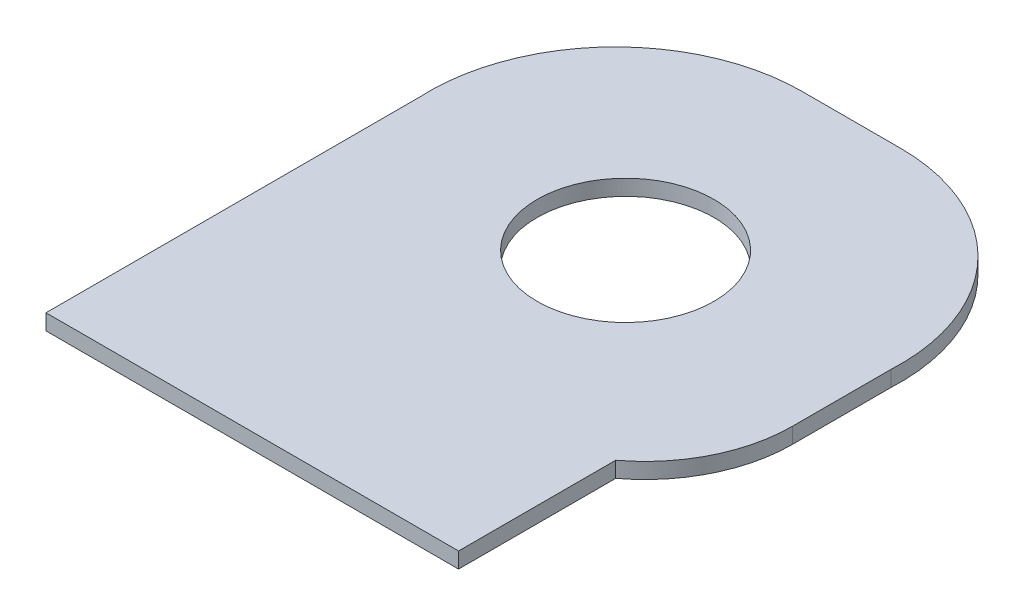
SolidWorks part; units mm, degrees
ref_plane "Plan de face" through (0, 0, 0) normal (0, 0, 1) x (1, 0, 0)
ref_plane "Plan de dessus" through (0, 0, 0) normal (0, 1, 0) x (1, 0, 0)
ref_plane "Plan de droite" through (0, 0, 0) normal (1, 0, 0) x (0, 0, -1)
sketch "Esquisse1" plane through (0, 0, 0) normal (0, 1, 0) x (1, 0, 0)
  line L0 (-24, 9) -> (-24, -29)
  line L1 (-24, -29) -> (18, -29)
  line L2 (18, -29) -> (18, -13)
  line L3 (24, -1) -> (24, 9)
  line L4 (-5, 29) -> (5, 29)
  line L5 (0, 29) -> (0, -29) construction
  line L6 (24, 0) -> (-24, 0) construction
  arc A0 (-5, 29) -> (-24, 9) centre (-5, 9.975) ccw
  arc A1 (5, 29) -> (24, 9) centre (5, 9.975) cw
  arc A2 (24, -1) -> (18, -13) centre (9, -1) cw
  circle A3 centre (0, 6) radius 9
  point P14 (0, 0)
  dimension "D1" = 42
  dimension "D2" = 38
  dimension "D8" = 18
  dimension "D3" = 16
  dimension "D4" = 10
  dimension "D5" = 10
  dimension "D6" = 48
  dimension "D7" = 58
  dimension "D9" = 23
extrude "Extrusion1" add sketch "Esquisse1" along normal blind 1.6
